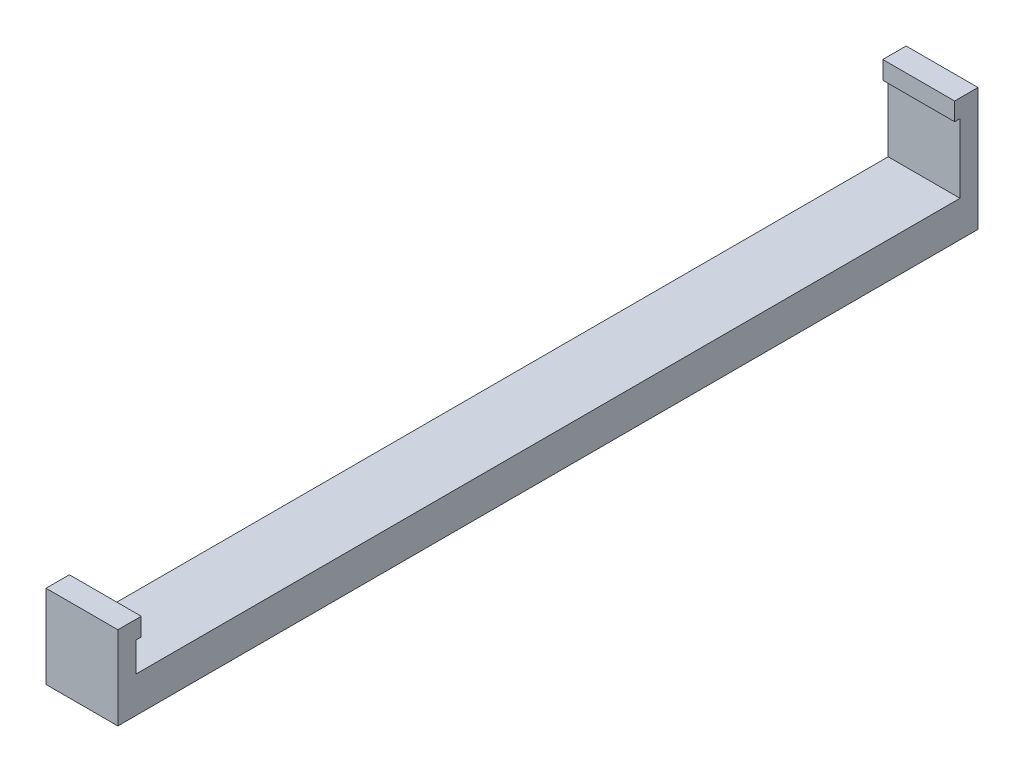
SolidWorks part; units mm, degrees
ref_plane "Front Plane" through (0, 0, 0) normal (0, 0, 1) x (1, 0, 0)
ref_plane "Top Plane" through (0, 0, 0) normal (0, 1, 0) x (1, 0, 0)
ref_plane "Right Plane" through (0, 0, 0) normal (1, 0, 0) x (0, 0, -1)
sketch "Sketch1" plane through (0, 0, 0) normal (0, 1, 0) x (1, 0, 0)
  line L2 (0, 0) -> (0, 114.68)
  line L4 (10, 0) -> (10, 114.68)
  line L5 (0, 0) -> (10, 114.68) construction
  line L6 (0, 114.68) -> (10, 0) construction
  line L7 (0, 114.68) -> (10, 114.68)
  line L13 (0, 0) -> (10, 0)
  point P4 (5, 57.34)
  dimension "D1" = 114.68
  dimension "D2" = 10
extrude "Boss-Extrude1" add sketch "Sketch1" along normal blind 5
sketch "Sketch3" plane through (10, 0, 0) normal (1, 0, 0) x (0, 0, -1)
  line L0 (0.75, 9.1) -> (0, 9.1)
  line L1 (0, 0) -> (-2.5, 0)
  line L2 (0, 0) -> (0, 9.1)
  line L4 (-2.5, 0) -> (-2.5, 9.1)
  line L5 (0, 0) -> (-2.5, 9.1) construction
  line L6 (0, 9.1) -> (-2.5, 0) construction
  line L7 (114.68, 0) -> (117.18, 0)
  line L8 (114.68, 0) -> (114.68, 14.6)
  line L10 (117.18, 0) -> (117.18, 14.6)
  line L11 (114.68, 0) -> (117.18, 14.6) construction
  line L12 (114.68, 14.6) -> (117.18, 0) construction
  line L14 (-2.5, 9.1) -> (-2.5, 11.6)
  line L15 (-2.5, 11.6) -> (0.75, 11.6)
  line L16 (0.75, 9.1) -> (0.75, 11.6)
  line L17 (-2.5, 9.1) -> (0.75, 11.6) construction
  line L18 (-2.5, 11.6) -> (0.75, 9.1) construction
  line L19 (113.93, 14.6) -> (114.68, 14.6)
  line L21 (117.18, 14.6) -> (117.18, 17.1)
  line L22 (117.18, 17.1) -> (113.93, 17.1)
  line L23 (113.93, 14.6) -> (113.93, 17.1)
  line L24 (117.18, 14.6) -> (113.93, 17.1) construction
  line L25 (117.18, 17.1) -> (113.93, 14.6) construction
  point P4 (-1.25, 4.55)
  point P10 (115.93, 7.3)
  point P15 (-0.875, 10.35)
  point P19 (115.555, 15.85)
  dimension "D1" = 2.5
  dimension "D2" = 2.5
  dimension "D3" = 9.1
  dimension "D4" = 14.6
  dimension "D5" = 2.5
  dimension "D6" = 3.25
  dimension "D7" = 2.5
  dimension "D8" = 3.25
extrude "Boss-Extrude2" add sketch "Sketch3" against normal through all
